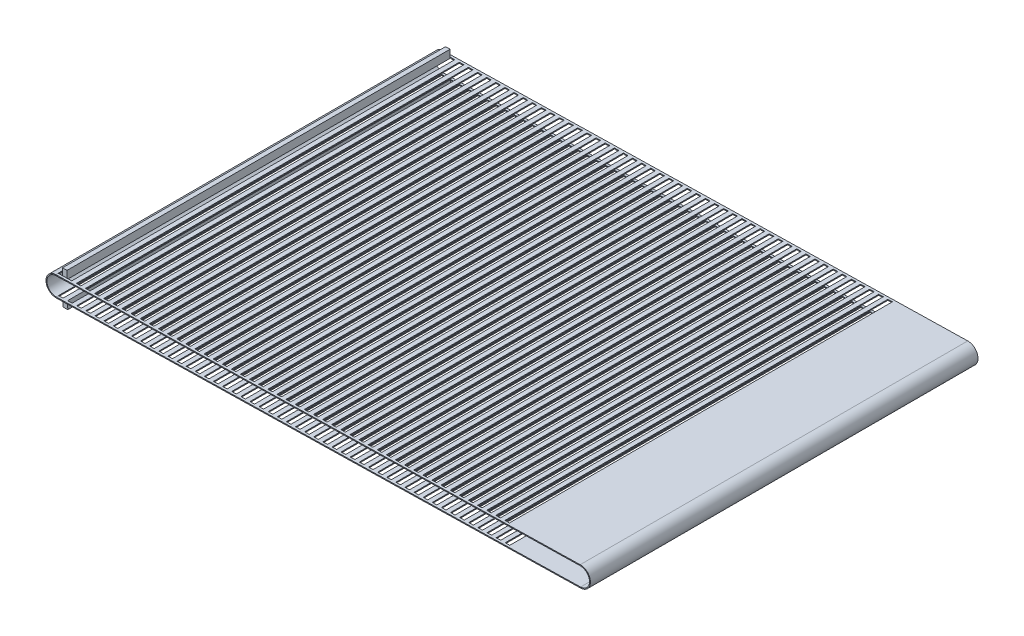
SolidWorks part; units mm, degrees
material "1023 Carbon Steel Sheet (SS)"
ref_plane "Front Plane" through (0, 0, 0) normal (0, 0, 1) x (1, 0, 0)
ref_plane "Top Plane" through (0, 0, 0) normal (0, 1, 0) x (1, 0, 0)
ref_plane "Right Plane" through (0, 0, 0) normal (1, 0, 0) x (0, 0, -1)
sketch "Sketch1" plane through (0, 0, 0) normal (0, 0, 1) x (1, 0, 0)
  line L0 (-610.1526, 0) -> (539.8474, 24.0385) construction
  line L1 (-610.5706, 19.9956) -> (539.4294, 44.0341)
  line L2 (-609.7346, -19.9956) -> (540.2654, 4.0428)
  arc A0 (-610.5706, 19.9956) -> (-609.7346, -19.9956) centre (-610.1526, 0) ccw
  arc A1 (540.2654, 4.0428) -> (539.4294, 44.0341) centre (539.8474, 24.0385) ccw
  point P2 (-35.1526, 12.0192)
  dimension "D2" = 20
  dimension "D1" = 1150
extrude "Extrude-Thin1" add sketch "Sketch1" along normal blind 850 thin thin type one direction wall 2
sketch "Sketch4" plane through (-0.7262, 34.7437, 0) normal (-0.0209, 0.9998, 0) x (0.9998, 0.0209, 0)
  line L0 (-610.0193, -850) -> (-610.0193, 0) construction
  line L1 (-610.0193, -5) -> (-600.0193, -5)
  line L2 (-610.0193, -5) -> (-610.0193, -845)
  line L3 (-610.0193, -845) -> (-600.0193, -845)
  line L4 (-600.0193, -5) -> (-600.0193, -845)
  line L5 (540.2319, 0) -> (-610.0193, 0) construction
  line L6 (540.2319, -850) -> (-610.0193, -850) construction
  line L7 (-590.0193, -5) -> (-590.0193, -845)
  line L8 (-580.0193, -5) -> (-580.0193, -845)
  line L9 (-590.0193, -845) -> (-580.0193, -845)
  line L10 (-590.0193, -5) -> (-580.0193, -5)
  line L11 (-570.0193, -5) -> (-570.0193, -845)
  line L12 (-560.0193, -5) -> (-560.0193, -845)
  line L13 (-570.0193, -845) -> (-560.0193, -845)
  line L14 (-570.0193, -5) -> (-560.0193, -5)
  line L15 (-550.0193, -5) -> (-550.0193, -845)
  line L16 (-540.0193, -5) -> (-540.0193, -845)
  line L17 (-550.0193, -845) -> (-540.0193, -845)
  line L18 (-550.0193, -5) -> (-540.0193, -5)
  line L19 (-530.0193, -5) -> (-530.0193, -845)
  line L20 (-520.0193, -5) -> (-520.0193, -845)
  line L21 (-530.0193, -845) -> (-520.0193, -845)
  line L22 (-530.0193, -5) -> (-520.0193, -5)
  line L23 (-510.0193, -5) -> (-510.0193, -845)
  line L24 (-500.0193, -5) -> (-500.0193, -845)
  line L25 (-510.0193, -845) -> (-500.0193, -845)
  line L26 (-510.0193, -5) -> (-500.0193, -5)
  line L27 (-490.0193, -5) -> (-490.0193, -845)
  line L28 (-480.0193, -5) -> (-480.0193, -845)
  line L29 (-490.0193, -845) -> (-480.0193, -845)
  line L30 (-490.0193, -5) -> (-480.0193, -5)
  line L31 (-470.0193, -5) -> (-470.0193, -845)
  line L32 (-460.0193, -5) -> (-460.0193, -845)
  line L33 (-470.0193, -845) -> (-460.0193, -845)
  line L34 (-470.0193, -5) -> (-460.0193, -5)
  line L35 (-450.0193, -5) -> (-450.0193, -845)
  line L36 (-440.0193, -5) -> (-440.0193, -845)
  line L37 (-450.0193, -845) -> (-440.0193, -845)
  line L38 (-450.0193, -5) -> (-440.0193, -5)
  line L39 (-430.0193, -5) -> (-430.0193, -845)
  line L40 (-420.0193, -5) -> (-420.0193, -845)
  line L41 (-430.0193, -845) -> (-420.0193, -845)
  line L42 (-430.0193, -5) -> (-420.0193, -5)
  line L43 (-410.0193, -5) -> (-410.0193, -845)
  line L44 (-400.0193, -5) -> (-400.0193, -845)
  line L45 (-410.0193, -845) -> (-400.0193, -845)
  line L46 (-410.0193, -5) -> (-400.0193, -5)
  line L47 (-390.0193, -5) -> (-390.0193, -845)
  line L48 (-380.0193, -5) -> (-380.0193, -845)
  line L49 (-390.0193, -845) -> (-380.0193, -845)
  line L50 (-390.0193, -5) -> (-380.0193, -5)
  line L51 (-370.0193, -5) -> (-370.0193, -845)
  line L52 (-360.0193, -5) -> (-360.0193, -845)
  line L53 (-370.0193, -845) -> (-360.0193, -845)
  line L54 (-370.0193, -5) -> (-360.0193, -5)
  line L55 (-350.0193, -5) -> (-350.0193, -845)
  line L56 (-340.0193, -5) -> (-340.0193, -845)
  line L57 (-350.0193, -845) -> (-340.0193, -845)
  line L58 (-350.0193, -5) -> (-340.0193, -5)
  line L59 (-330.0193, -5) -> (-330.0193, -845)
  line L60 (-320.0193, -5) -> (-320.0193, -845)
  line L61 (-330.0193, -845) -> (-320.0193, -845)
  line L62 (-330.0193, -5) -> (-320.0193, -5)
  line L63 (-310.0193, -5) -> (-310.0193, -845)
  line L64 (-300.0193, -5) -> (-300.0193, -845)
  line L65 (-310.0193, -845) -> (-300.0193, -845)
  line L66 (-310.0193, -5) -> (-300.0193, -5)
  line L67 (-290.0193, -5) -> (-290.0193, -845)
  line L68 (-280.0193, -5) -> (-280.0193, -845)
  line L69 (-290.0193, -845) -> (-280.0193, -845)
  line L70 (-290.0193, -5) -> (-280.0193, -5)
  line L71 (-270.0193, -5) -> (-270.0193, -845)
  line L72 (-260.0193, -5) -> (-260.0193, -845)
  line L73 (-270.0193, -845) -> (-260.0193, -845)
  line L74 (-270.0193, -5) -> (-260.0193, -5)
  line L75 (-250.0193, -5) -> (-250.0193, -845)
  line L76 (-240.0193, -5) -> (-240.0193, -845)
  line L77 (-250.0193, -845) -> (-240.0193, -845)
  line L78 (-250.0193, -5) -> (-240.0193, -5)
  line L79 (-230.0193, -5) -> (-230.0193, -845)
  line L80 (-220.0193, -5) -> (-220.0193, -845)
  line L81 (-230.0193, -845) -> (-220.0193, -845)
  line L82 (-230.0193, -5) -> (-220.0193, -5)
  line L83 (-210.0193, -5) -> (-210.0193, -845)
  line L84 (-200.0193, -5) -> (-200.0193, -845)
  line L85 (-210.0193, -845) -> (-200.0193, -845)
  line L86 (-210.0193, -5) -> (-200.0193, -5)
  line L87 (-190.0193, -5) -> (-190.0193, -845)
  line L88 (-180.0193, -5) -> (-180.0193, -845)
  line L89 (-190.0193, -845) -> (-180.0193, -845)
  line L90 (-190.0193, -5) -> (-180.0193, -5)
  line L91 (-170.0193, -5) -> (-170.0193, -845)
  line L92 (-160.0193, -5) -> (-160.0193, -845)
  line L93 (-170.0193, -845) -> (-160.0193, -845)
  line L94 (-170.0193, -5) -> (-160.0193, -5)
  line L95 (-150.0193, -5) -> (-150.0193, -845)
  line L96 (-140.0193, -5) -> (-140.0193, -845)
  line L97 (-150.0193, -845) -> (-140.0193, -845)
  line L98 (-150.0193, -5) -> (-140.0193, -5)
  line L99 (-130.0193, -5) -> (-130.0193, -845)
  line L100 (-120.0193, -5) -> (-120.0193, -845)
  line L101 (-130.0193, -845) -> (-120.0193, -845)
  line L102 (-130.0193, -5) -> (-120.0193, -5)
  line L103 (-110.0193, -5) -> (-110.0193, -845)
  line L104 (-100.0193, -5) -> (-100.0193, -845)
  line L105 (-110.0193, -845) -> (-100.0193, -845)
  line L106 (-110.0193, -5) -> (-100.0193, -5)
  line L107 (-90.0193, -5) -> (-90.0193, -845)
  line L108 (-80.0193, -5) -> (-80.0193, -845)
  line L109 (-90.0193, -845) -> (-80.0193, -845)
  line L110 (-90.0193, -5) -> (-80.0193, -5)
  line L111 (-70.0193, -5) -> (-70.0193, -845)
  line L112 (-60.0193, -5) -> (-60.0193, -845)
  line L113 (-70.0193, -845) -> (-60.0193, -845)
  line L114 (-70.0193, -5) -> (-60.0193, -5)
  line L115 (-50.0193, -5) -> (-50.0193, -845)
  line L116 (-40.0193, -5) -> (-40.0193, -845)
  line L117 (-50.0193, -845) -> (-40.0193, -845)
  line L118 (-50.0193, -5) -> (-40.0193, -5)
  line L119 (-30.0193, -5) -> (-30.0193, -845)
  line L120 (-20.0193, -5) -> (-20.0193, -845)
  line L121 (-30.0193, -845) -> (-20.0193, -845)
  line L122 (-30.0193, -5) -> (-20.0193, -5)
  line L123 (-10.0193, -5) -> (-10.0193, -845)
  line L124 (-0.0193, -5) -> (-0.0193, -845)
  line L125 (-10.0193, -845) -> (-0.0193, -845)
  line L126 (-10.0193, -5) -> (-0.0193, -5)
  line L127 (9.9807, -5) -> (9.9807, -845)
  line L128 (19.9807, -5) -> (19.9807, -845)
  line L129 (9.9807, -845) -> (19.9807, -845)
  line L130 (9.9807, -5) -> (19.9807, -5)
  line L131 (29.9807, -5) -> (29.9807, -845)
  line L132 (39.9807, -5) -> (39.9807, -845)
  line L133 (29.9807, -845) -> (39.9807, -845)
  line L134 (29.9807, -5) -> (39.9807, -5)
  line L135 (49.9807, -5) -> (49.9807, -845)
  line L136 (59.9807, -5) -> (59.9807, -845)
  line L137 (49.9807, -845) -> (59.9807, -845)
  line L138 (49.9807, -5) -> (59.9807, -5)
  line L139 (69.9807, -5) -> (69.9807, -845)
  line L140 (79.9807, -5) -> (79.9807, -845)
  line L141 (69.9807, -845) -> (79.9807, -845)
  line L142 (69.9807, -5) -> (79.9807, -5)
  line L143 (89.9807, -5) -> (89.9807, -845)
  line L144 (99.9807, -5) -> (99.9807, -845)
  line L145 (89.9807, -845) -> (99.9807, -845)
  line L146 (89.9807, -5) -> (99.9807, -5)
  line L147 (109.9807, -5) -> (109.9807, -845)
  line L148 (119.9807, -5) -> (119.9807, -845)
  line L149 (109.9807, -845) -> (119.9807, -845)
  line L150 (109.9807, -5) -> (119.9807, -5)
  line L151 (129.9807, -5) -> (129.9807, -845)
  line L152 (139.9807, -5) -> (139.9807, -845)
  line L153 (129.9807, -845) -> (139.9807, -845)
  line L154 (129.9807, -5) -> (139.9807, -5)
  line L155 (149.9807, -5) -> (149.9807, -845)
  line L156 (159.9807, -5) -> (159.9807, -845)
  line L157 (149.9807, -845) -> (159.9807, -845)
  line L158 (149.9807, -5) -> (159.9807, -5)
  line L159 (169.9807, -5) -> (169.9807, -845)
  line L160 (179.9807, -5) -> (179.9807, -845)
  line L161 (169.9807, -845) -> (179.9807, -845)
  line L162 (169.9807, -5) -> (179.9807, -5)
  line L163 (189.9807, -5) -> (189.9807, -845)
  line L164 (199.9807, -5) -> (199.9807, -845)
  line L165 (189.9807, -845) -> (199.9807, -845)
  line L166 (189.9807, -5) -> (199.9807, -5)
  line L167 (209.9807, -5) -> (209.9807, -845)
  line L168 (219.9807, -5) -> (219.9807, -845)
  line L169 (209.9807, -845) -> (219.9807, -845)
  line L170 (209.9807, -5) -> (219.9807, -5)
  line L171 (229.9807, -5) -> (229.9807, -845)
  line L172 (239.9807, -5) -> (239.9807, -845)
  line L173 (229.9807, -845) -> (239.9807, -845)
  line L174 (229.9807, -5) -> (239.9807, -5)
  line L175 (249.9807, -5) -> (249.9807, -845)
  line L176 (259.9807, -5) -> (259.9807, -845)
  line L177 (249.9807, -845) -> (259.9807, -845)
  line L178 (249.9807, -5) -> (259.9807, -5)
  line L179 (269.9807, -5) -> (269.9807, -845)
  line L180 (279.9807, -5) -> (279.9807, -845)
  line L181 (269.9807, -845) -> (279.9807, -845)
  line L182 (269.9807, -5) -> (279.9807, -5)
  line L183 (289.9807, -5) -> (289.9807, -845)
  line L184 (299.9807, -5) -> (299.9807, -845)
  line L185 (289.9807, -845) -> (299.9807, -845)
  line L186 (289.9807, -5) -> (299.9807, -5)
  line L187 (309.9807, -5) -> (309.9807, -845)
  line L188 (319.9807, -5) -> (319.9807, -845)
  line L189 (309.9807, -845) -> (319.9807, -845)
  line L190 (309.9807, -5) -> (319.9807, -5)
  line L191 (329.9807, -5) -> (329.9807, -845)
  line L192 (339.9807, -5) -> (339.9807, -845)
  line L193 (329.9807, -845) -> (339.9807, -845)
  line L194 (329.9807, -5) -> (339.9807, -5)
  line L195 (349.9807, -5) -> (349.9807, -845)
  line L196 (359.9807, -5) -> (359.9807, -845)
  line L197 (349.9807, -845) -> (359.9807, -845)
  line L198 (349.9807, -5) -> (359.9807, -5)
  line L199 (369.9807, -5) -> (369.9807, -845)
  line L200 (379.9807, -5) -> (379.9807, -845)
  line L201 (369.9807, -845) -> (379.9807, -845)
  line L202 (369.9807, -5) -> (379.9807, -5)
  dimension "D1" = 5
  dimension "D2" = 5
  dimension "D3" = 10
  dimension "D4" = 50
extrude "Cut-Extrude1" cut sketch "Sketch4" against normal blind 100
sketch "Sketch5" plane through (-0.7262, 34.7437, 0) normal (-0.0209, 0.9998, 0) x (0.9998, 0.0209, 0)
  line L1 (-600.0193, -5) -> (-590.0193, -5)
  line L2 (-600.0193, -5) -> (-600.0193, -845)
  line L3 (-600.0193, -845) -> (-590.0193, -845)
  line L4 (-590.0193, -5) -> (-590.0193, -845)
extrude "Boss-Extrude2" add sketch "Sketch5" along normal blind 15
sketch "Sketch6" plane through (0.1933, -9.2467, 0) normal (0.0209, -0.9998, 0) x (0.9998, 0.0209, 0)
  line L1 (-600.0193, 845) -> (-590.0193, 845)
  line L2 (-600.0193, 845) -> (-600.0193, 5)
  line L3 (-600.0193, 5) -> (-590.0193, 5)
  line L4 (-590.0193, 845) -> (-590.0193, 5)
extrude "Boss-Extrude3" add sketch "Sketch6" along normal blind 15
